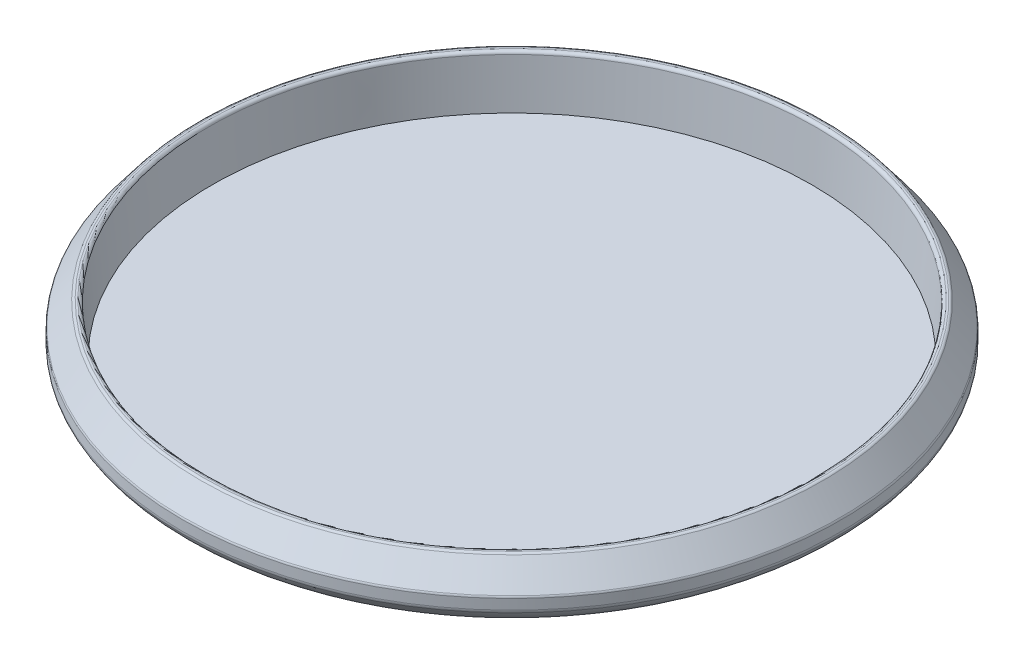
SolidWorks part; units mm, degrees
ref_plane "Front (XY)" through (0, 0, 0) normal (0, 0, 1) x (1, 0, 0)
ref_plane "Top (XZ)" through (0, 0, 0) normal (0, 1, 0) x (1, 0, 0)
ref_plane "Right (YZ)" through (0, 0, 0) normal (1, 0, 0) x (0, 0, -1)
sketch "Sketch1" plane through (0, 0, 0) normal (0, 1, 0) x (1, 0, 0)
  circle A0 centre (0, 0) radius 95
  dimension "D1" = 190
extrude "Boss-Extrude1" add sketch "Sketch1" along normal blind 1.5
sketch "Sketch2" plane through (0, 0, 0) normal (0, 0, 1) x (1, 0, 0)
  line L0 (95, 0) -> (106, 0) construction
  line L1 (95, 1.5) -> (96.4042, 17.55)
  line L2 (95, 0) -> (95, 1.5) construction
  line L3 (96.4042, 17.55) -> (98.4042, 17.55)
  line L4 (98.4042, 17.55) -> (98.4042, 8.55) construction
  line L5 (98.4042, 17.55) -> (104.4611, 9.593)
  line L6 (104.4611, 9.593) -> (104.4611, 5.593)
  line L8 (95, 1.5) -> (95, 0)
  line L9 (0, 0) -> (0, 11.5081) construction
  arc A0 (95, 0) -> (104.4611, 5.593) centre (95.7578, 9.5168) ccw
  dimension "D1" = 11
  dimension "D2" = 16.05
  dimension "D3" = 185
  dimension "D4" = 2
  dimension "D5" = 9
  dimension "D6" = 10
  dimension "D7" = 4
revolve "Revolve1" add sketch "Sketch2" angle 360 about L9
fillet "Fillet1" radius 1 2 edges at (0, 17.55, -96.4042) (0, 17.55, -98.4042)
fillet "Fillet2" radius 1 1 edges at (0, 9.593, -104.4611)
fillet "Fillet4" radius 2 1 edges at (0, 5.593, -104.4611)
